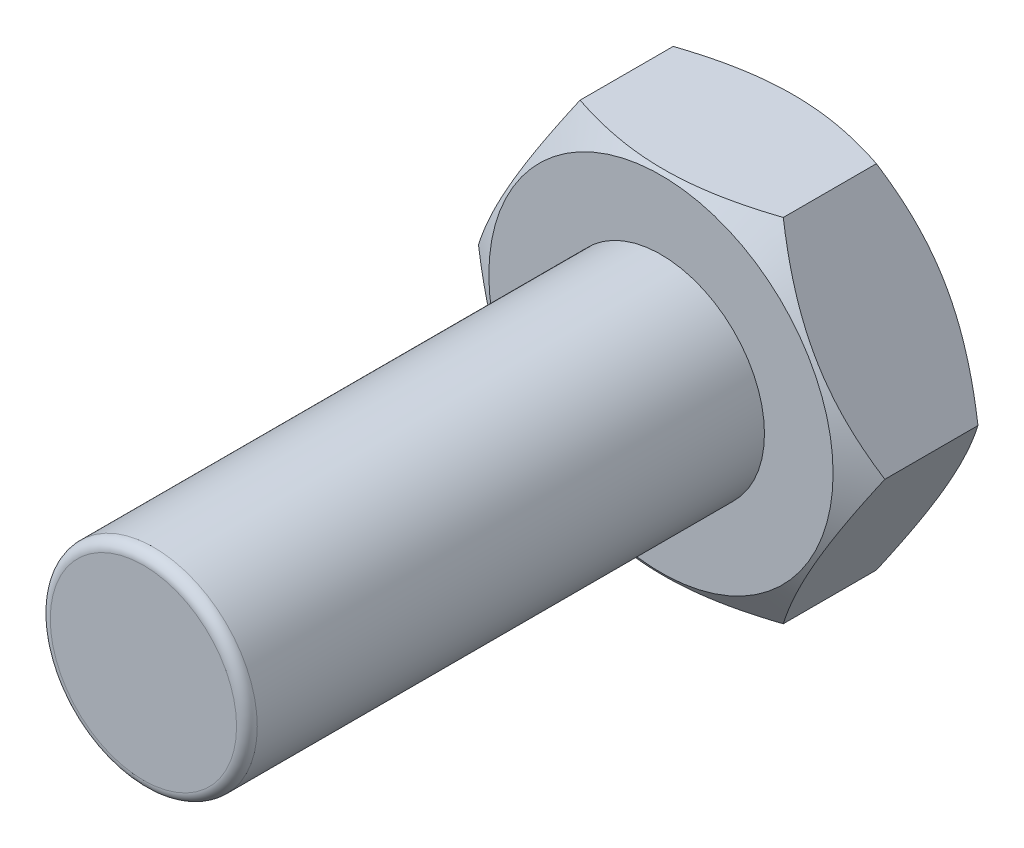
SolidWorks part; units mm, degrees
material "1.0036 (S235JRG1)"
ref_plane "Ön Düzlem" through (0, 0, 0) normal (0, 0, 1) x (1, 0, 0)
ref_plane "Üst Düzlem" through (0, 0, 0) normal (0, 1, 0) x (1, 0, 0)
ref_plane "Sağ Düzlem" through (0, 0, 0) normal (1, 0, 0) x (0, 0, -1)
sketch "Çizim1" plane through (0, 0, 0) normal (0, 0, 1) x (1, 0, 0)
  line L1 (9.815, 0) -> (4.9075, 8.5)
  line L2 (4.9075, 8.5) -> (-4.9075, 8.5)
  line L3 (-4.9075, 8.5) -> (-9.815, 0)
  line L4 (-9.815, 0) -> (-4.9075, -8.5)
  line L5 (-4.9075, -8.5) -> (4.9075, -8.5)
  line L6 (4.9075, -8.5) -> (9.815, 0)
  circle A0 centre (0, 0) radius 8.5 construction
  dimension "D1" = 17
extrude "Yükseklik-Ekstrüzyon1" add sketch "Çizim1" along normal blind 6.5
sketch "Çizim2" plane through (0, 0, 6.5) normal (0, 0, 1) x (1, 0, 0)
  circle A0 centre (0, 0) radius 5
  dimension "D1" = 10
extrude "Yükseklik-Ekstrüzyon2" add sketch "Çizim2" along normal blind 25
cosmetic thread "Kozmetik Diş Açma1" parameters "D2"=8.344
sketch "Çizim3" plane through (0, 0, 0) normal (0, 1, 0) x (1, 0, 0)
  line L0 (-9.815, 0) -> (-8.315, 0)
  line L1 (-4.9075, 0) -> (-9.815, 0) construction
  line L2 (-8.315, 0) -> (-9.815, -1)
  line L3 (-9.815, -6.5) -> (-9.815, 0) construction
  line L4 (-9.815, -1) -> (-9.815, 0)
  line L9 (-9.815, -6.5) -> (-9.815, -5.5)
  line L10 (-9.815, -5.5) -> (-8.315, -6.5)
  line L11 (-4.9075, -6.5) -> (-9.815, -6.5) construction
  line L12 (-8.315, -6.5) -> (-9.815, -6.5)
  line L13 (0, 0) -> (0, -6.5) construction
  line L14 (-5, -6.5) -> (5, -6.5) construction
  dimension "D1" = 1.5
  dimension "D2" = 1
  dimension "D3" = 1
  dimension "D4" = 1.5
revolve "Kes-Döndür1" cut sketch "Çizim3" angle 360 about L13
fillet "Radyus1" radius 0.5 1 edges at (5, 0, 31.5)
